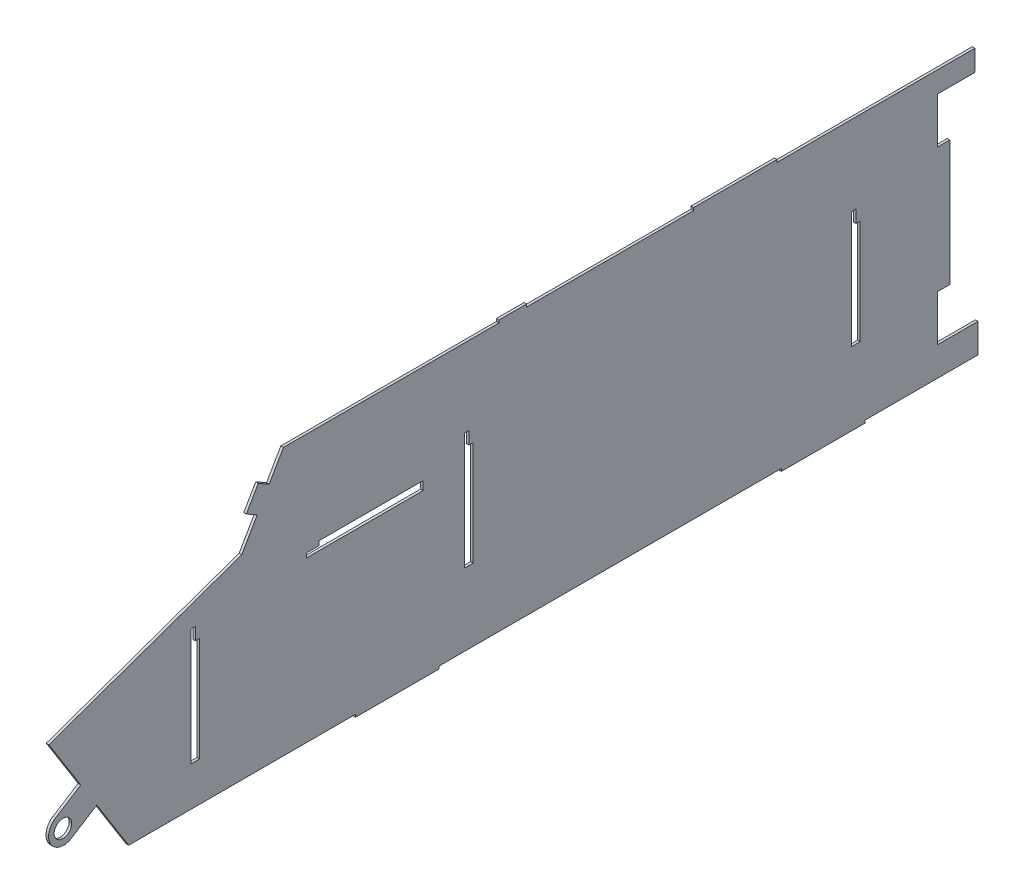
SolidWorks part; units mm, degrees
ref_plane "Front Plane" through (0, 0, 0) normal (0, 0, 1) x (1, 0, 0)
ref_plane "Top Plane" through (0, 0, 0) normal (0, 1, 0) x (1, 0, 0)
ref_plane "Right Plane" through (0, 0, 0) normal (1, 0, 0) x (0, 0, -1)
sketch "Sketch1" plane through (0, 0, 0) normal (1, 0, 0) x (0, 0, -1)
  line L0 (-239.3196, 33.1497) -> (-103.7996, 33.1497)
  line L1 (-103.7996, 33.1497) -> (-103.7996, 43.1497)
  line L2 (-103.7996, 43.1497) -> (-224.7996, 43.1497)
  line L3 (-224.7996, 43.1497) -> (-224.7996, 38.1497)
  line L4 (-224.7996, 38.1497) -> (-239.3196, 38.1497)
  line L5 (-239.3196, 38.1497) -> (-239.3196, 33.1497)
  line L6 (-55.934, 66.8564) -> (-55.9339, -68.6636)
  line L7 (-55.9339, -68.6636) -> (-45.9339, -68.6636)
  line L8 (-45.9339, -68.6636) -> (-45.934, 52.3364)
  line L9 (-45.934, 52.3364) -> (-50.9339, 52.3364)
  line L10 (-50.9339, 52.3364) -> (-50.9339, 66.8564)
  line L11 (-50.9339, 66.8564) -> (-55.934, 66.8564)
  line L12 (-372.9995, 28.8099) -> (-372.9994, -106.7101)
  line L13 (-372.9994, -106.7101) -> (-362.9994, -106.7101)
  line L14 (-362.9994, -106.7101) -> (-362.9995, 14.2899)
  line L15 (-362.9995, 14.2899) -> (-367.9995, 14.2899)
  line L16 (-367.9995, 14.2899) -> (-367.9995, 28.8099)
  line L17 (-367.9995, 28.8099) -> (-372.9995, 28.8099)
  line L18 (392.8366, 64.8416) -> (392.8367, -70.6784)
  line L19 (392.8367, -70.6784) -> (402.8367, -70.6784)
  line L20 (402.8367, -70.6784) -> (402.8366, 50.3216)
  line L21 (402.8366, 50.3216) -> (397.8366, 50.3216)
  line L22 (397.8366, 50.3216) -> (397.8366, 64.8416)
  line L23 (397.8366, 64.8416) -> (392.8366, 64.8416)
  line L24 (16.1049, 157.4929) -> (16.1049, 160.4929)
  line L25 (209.706, 157.4929) -> (16.1049, 157.4929)
  line L26 (209.706, 160.4929) -> (209.706, 157.4929)
  line L27 (209.706, 160.4929) -> (306.5056, 160.4929)
  line L28 (306.5056, 157.4929) -> (306.5056, 160.4929)
  line L29 (535.7698, 157.4929) -> (306.5056, 157.4929)
  line L30 (535.5764, 133.1317) -> (535.7698, 157.4929)
  line L31 (492.2881, 133.1317) -> (535.5764, 133.1317)
  line L32 (492.2881, 79.8855) -> (492.2881, 133.1317)
  line L33 (506.8098, 79.8855) -> (492.2881, 79.8855)
  line L34 (506.8099, -65.3132) -> (506.8098, 79.8855)
  line L35 (492.2965, -65.3132) -> (506.8099, -65.3132)
  line L36 (492.2965, -118.5545) -> (492.2965, -65.3132)
  line L37 (539.3515, -152.2651) -> (539.3515, -118.5545)
  line L38 (408.1977, -155.2651) -> (408.1977, -152.2651)
  line L39 (408.1977, -155.2651) -> (311.3997, -155.2651)
  line L40 (311.3997, -152.2651) -> (311.3997, -155.2651)
  line L41 (-85.4869, -152.2652) -> (311.3997, -152.2651)
  line L42 (-85.4869, -155.2652) -> (-85.4869, -152.2652)
  line L43 (-85.4869, -155.2652) -> (-182.2882, -155.2652)
  line L44 (-182.2882, -152.2652) -> (-182.2882, -155.2652)
  line L45 (-445.308, -152.2652) -> (-182.2882, -152.2652)
  line L46 (-482.2784, -93.448) -> (-445.308, -152.2652)
  line L47 (-511.4535, -111.9465) -> (-482.2784, -93.448)
  line L48 (-500.8353, -63.9277) -> (-529.907, -82.2912)
  line L49 (-537.8525, -5.0389) -> (-500.8353, -63.9277)
  line L50 (-314.2109, 73.9576) -> (-537.8525, -5.0389)
  line L51 (-296.3543, 104.8152) -> (-314.2109, 73.9576)
  line L52 (-308.9201, 112.0952) -> (-296.3543, 104.8152)
  line L53 (-295.0471, 136.0696) -> (-308.9201, 112.0952)
  line L54 (-282.4813, 128.7946) -> (-295.0471, 136.0696)
  line L55 (-265.8786, 157.4928) -> (-282.4813, 128.7946)
  line L56 (-15.9365, 157.4928) -> (-265.8786, 157.4928)
  line L57 (-15.9365, 160.4928) -> (-15.9365, 157.4928)
  line L58 (-15.9365, 160.4928) -> (16.1049, 160.4929)
  line L59 (408.1977, -152.2651) -> (539.3515, -152.2651)
  line L60 (539.3515, -118.5545) -> (492.2965, -118.5545)
  spline S0 degree 3 poles (-521.5282, -107.4528) (-527.1274, -107.4528) (-531.6679, -102.9207) (-531.6679, -97.3148) knots 0 0 0 0 0.333333 0.333333 0.333333 0.333333
  spline S1 degree 3 poles (-531.6679, -97.3148) (-531.6679, -91.7172) (-527.1291, -87.1751) (-521.5282, -87.1751) knots 0.333333 0.333333 0.333333 0.333333 1 1 1 1
  spline S2 degree 3 poles (-521.5282, -87.1751) (-515.9273, -87.1751) (-511.3902, -91.7139) (-511.3902, -97.3148) knots 0 0 0 0 0.333333 0.333333 0.333333 0.333333
  spline S3 degree 3 poles (-511.3902, -97.3148) (-511.3902, -102.9207) (-515.9289, -107.4528) (-521.5282, -107.4528) knots 0.333333 0.333333 0.333333 0.333333 1 1 1 1
  spline S4 degree 3 poles (-535.5096, -106.349) (-530.4139, -114.5394) (-519.644, -117.0489) (-511.4535, -111.9465) knots 0 0 0 0 1 1 1 1
  spline S5 degree 3 poles (-529.907, -82.2912) (-538.0975, -87.3835) (-540.6053, -98.1585) (-535.5096, -106.349) knots 0 0 0 0 1 1 1 1
extrude "Boss-Extrude1" add sketch "Sketch1" along normal blind 3
